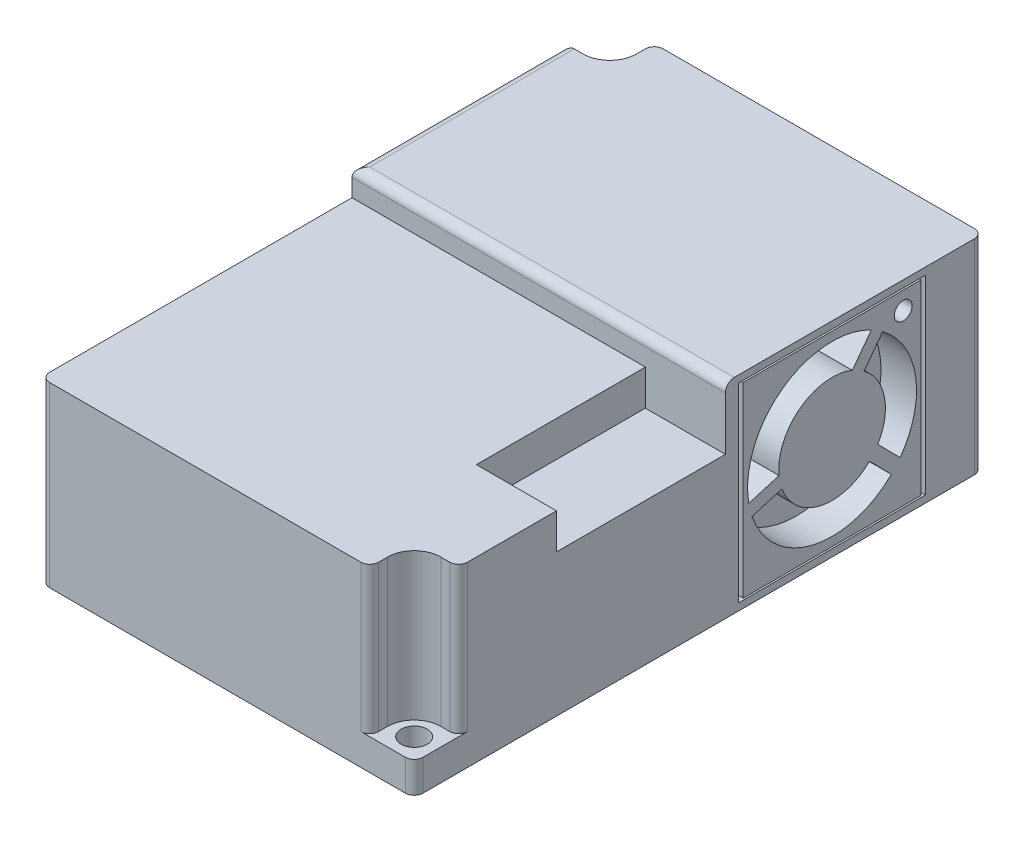
SolidWorks part; units mm, degrees
ref_plane "Front Plane" through (0, 0, 0) normal (0, 0, 1) x (1, 0, 0)
ref_plane "Top Plane" through (0, 0, 0) normal (0, 1, 0) x (1, 0, 0)
ref_plane "Right Plane" through (0, 0, 0) normal (1, 0, 0) x (0, 0, -1)
sketch "Sketch1" plane through (0, 0, 0) normal (0, 1, 0) x (1, 0, 0)
  line L0 (0, -55) -> (0, 55) construction
  line L1 (-21, 32) -> (21, 32)
  line L2 (-21, 32) -> (-21, -32)
  line L3 (-21, -32) -> (21, -32)
  line L4 (21, 32) -> (21, -32)
  line L5 (-55, 0) -> (55, 0) construction
  dimension "D1" = 21
  dimension "D2" = 42
  dimension "D3" = 32
  dimension "D4" = 64
extrude "Boss-Extrude1" add sketch "Sketch1" along normal blind 20
sketch "Sketch4" plane through (0, 20, 0) normal (0, 1, 0) x (1, 0, 0)
  line L0 (-21, 3) -> (21, 3) construction
  line L1 (-21, 32) -> (-21, -32) construction
  line L2 (21, -32) -> (21, 32) construction
  line L3 (21, 32) -> (-21, 32) construction
  line L5 (-21, 32) -> (21, 32)
  line L6 (-21, 32) -> (-21, 3)
  line L7 (-21, 3) -> (21, 3)
  line L8 (21, 32) -> (21, 3)
  dimension "D1" = 29
extrude "Boss-Extrude2" add sketch "Sketch4" along normal blind 3
sketch "Sketch5" plane through (0, 20, 0) normal (0, 1, 0) x (1, 0, 0)
  line L0 (21, 3) -> (12, 3)
  line L1 (-21, 3) -> (21, 3) construction
  line L2 (12, 3) -> (12, -16)
  line L3 (12, -16) -> (21, -16)
  line L4 (21, -32) -> (21, 3) construction
  line L5 (21, -16) -> (21, 3)
  dimension "D1" = 9
  dimension "D2" = 19
extrude "Cut-Extrude1" cut sketch "Sketch5" against normal blind 4
sketch "Sketch6" plane through (0, 0, 0) normal (0, 1, 0) x (1, 0, 0)
  line L9 (-21, 32) -> (-16, 32)
  line L10 (-21, 32) -> (-21, 27)
  line L11 (-21, 27) -> (-16, 27)
  line L12 (-16, 32) -> (-16, 27)
  line L13 (21, -32) -> (16, -32)
  line L14 (21, -32) -> (21, -27)
  line L15 (21, -27) -> (16, -27)
  line L16 (16, -32) -> (16, -27)
  dimension "D5" = 5
  dimension "D6" = 5
  dimension "D7" = 5
  dimension "D8" = 5
extrude "Cut-Extrude2" cut sketch "Sketch6" along normal up to next from offset 3.5
fillet "Fillet1" radius 3 2 edges at (-16, 13.25, -27) (16, 11.75, 27)
fillet "Fillet2" radius 1 10 edges at (21, 1.75, 32) (-21, 1.75, -32) (-21, 13.25, -27) (-16, 13.25, -32) (21, 11.5, -32) (-21, 10, 32) (16, 11.75, 32) (21, 11.75, 27) (0, 23, -3) (-21, 23, -15)
sketch "Sketch7" plane through (0, 3.5, 0) normal (0, 1, 0) x (1, 0, 0)
  line L1 (-15, 32) -> (-20, 32) construction
  line L2 (-21, 31) -> (-21, 26) construction
  line L3 (21, -31) -> (21, -26) construction
  line L4 (15, -32) -> (20, -32) construction
  circle A0 centre (18.5, -29.5) radius 1.4711
  circle A1 centre (-18.5, 29.5) radius 1.4155
  point P10 (21, -28.5)
  dimension "D1" = 2.5
  dimension "D2" = 2.5
  dimension "D3" = 2.5
  dimension "D4" = 2.5
extrude "Cut-Extrude3" cut sketch "Sketch7" against normal through all
sketch "Sketch8" plane through (21, 0, 0) normal (1, 0, 0) x (0, 0, -1)
  line L0 (3, 22) -> (3, 16) construction
  line L1 (5, 22) -> (25, 22)
  line L2 (5, 22) -> (5, 1)
  line L3 (5, 1) -> (25, 1)
  line L4 (25, 22) -> (25, 1)
  line L5 (4, 23) -> (31, 23) construction
  line L6 (23.1, 0) -> (-23.1, 0) construction
  line L7 (15, 22) -> (15, 1) construction
  line L8 (19.4156, 19.9114) -> (17.2772, 17.0511)
  line L9 (20.6883, 19.1087) -> (18.5926, 16.3055)
  line L10 (5.6336, 9.9122) -> (9.0278, 10.923)
  line L11 (6.0007, 8.4564) -> (9.3587, 9.4564)
  line L12 (19.2064, 7.2215) -> (21.6602, 4.7257)
  line L13 (20.1425, 8.4089) -> (22.6463, 5.8623)
  line L15 (4.5, 22.2) -> (25.5, 22.2)
  line L16 (4.5, 22.2) -> (4.5, 0.8)
  line L17 (4.5, 0.8) -> (25.5, 0.8)
  line L18 (25.5, 22.2) -> (25.5, 0.8)
  arc A0 (19.4156, 19.9114) -> (5.6336, 9.9122) centre (15, 11.5) ccw
  arc A1 (17.2772, 17.0511) -> (9.0278, 10.923) centre (15, 11.5) ccw
  circle A2 centre (23, 20) radius 1
  arc A3 (9.3587, 9.4564) -> (19.2064, 7.2215) centre (15, 11.5) ccw
  arc A4 (20.1425, 8.4089) -> (18.5926, 16.3055) centre (15, 11.5) ccw
  arc A5 (22.6463, 5.8623) -> (20.6883, 19.1087) centre (15, 11.5) ccw
  arc A6 (6.0007, 8.4564) -> (21.6602, 4.7257) centre (15, 11.5) ccw
  dimension "D5" = 19
  dimension "D6" = 12
  dimension "D9" = 2
  dimension "D1" = 2
  dimension "D2" = 1
  dimension "D3" = 1
  dimension "D4" = 20
  dimension "D7" = 2
  dimension "D8" = 2
  dimension "D10" = 1.5
  dimension "D11" = 1.5
  dimension "D12" = 1.5
  dimension "D13" = 0.2
  dimension "D14" = 0.5
  dimension "D15" = 0.5
  dimension "D16" = 0.2
extrude "Cut-Extrude5" cut sketch "Sketch8" against normal blind 4 contours L18 L15 L16 L17 L1 L4 L3 L2 | A2 | A0 L7 A1 L8 | L7 A0 L10 A1 | L7 A3 L11 A6 | A3 L7 A6 L12 | L13 A5 L9 A4
sketch "Sketch10" plane through (-21, 0, 0) normal (-1, 0, 0) x (0, 0, 1)
  line L0 (-26, 22) -> (-26, 3.5) construction
  line L1 (-22, 20) -> (-11, 20)
  line L2 (-22, 20) -> (-22, 15.5)
  line L3 (-22, 15.5) -> (-11, 15.5)
  line L4 (-11, 20) -> (-11, 15.5)
  line L5 (-26, 23) -> (-4, 23) construction
  dimension "D1" = 4
  dimension "D2" = 3
  dimension "D3" = 4.5
  dimension "D4" = 11
extrude "Cut-Extrude6" cut sketch "Sketch10" against normal blind 4
